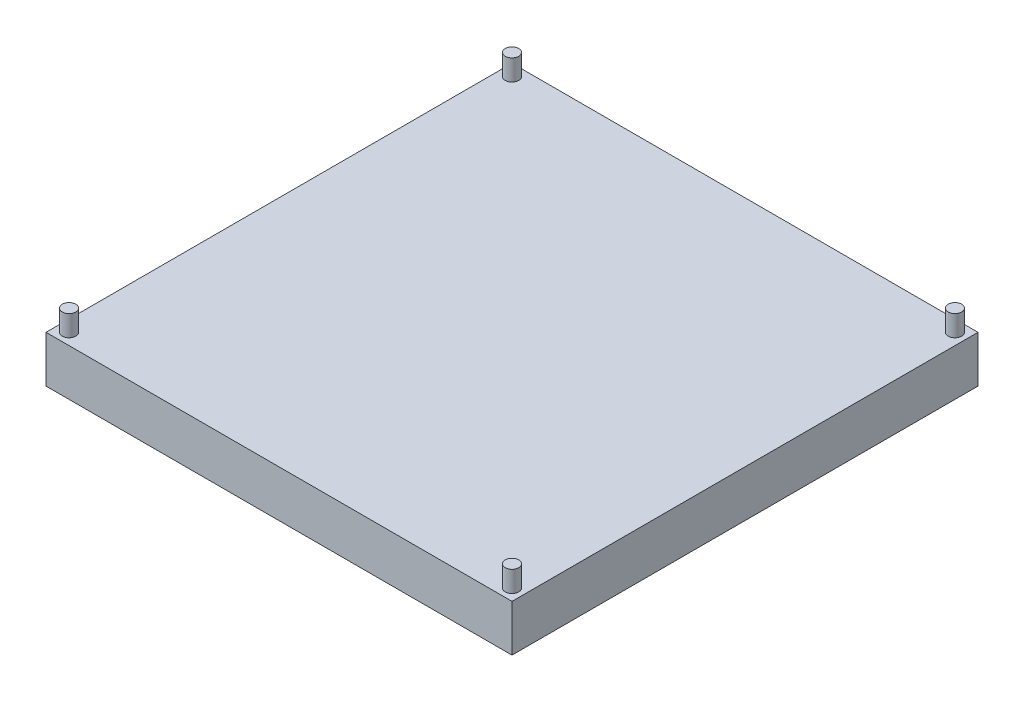
SolidWorks part; units mm, degrees
ref_plane "Front Plane" through (0, 0, 0) normal (0, 0, 1) x (1, 0, 0)
ref_plane "Top Plane" through (0, 0, 0) normal (0, 1, 0) x (1, 0, 0)
ref_plane "Right Plane" through (0, 0, 0) normal (1, 0, 0) x (0, 0, -1)
sketch "Sketch1" plane through (0, 0, 0) normal (0, 1, 0) x (1, 0, 0)
  line L1 (-25.4, -25.4) -> (25.4, -25.4)
  line L2 (-25.4, -25.4) -> (-25.4, 25.4)
  line L3 (-25.4, 25.4) -> (25.4, 25.4)
  line L4 (25.4, -25.4) -> (25.4, 25.4)
  line L5 (-25.4, -25.4) -> (25.4, 25.4) construction
  line L6 (-25.4, 25.4) -> (25.4, -25.4) construction
  point P0 (0, 0)
  dimension "D1" = 50.8
  dimension "D2" = 50.8
extrude "Boss-Extrude1" add sketch "Sketch1" along normal blind 5.08
sketch "Sketch11" plane through (0, 5.08, 0) normal (0, 1, 0) x (1, 0, 0)
  line L5 (-22.86, -22.86) -> (22.86, 22.86) construction
  line L6 (-22.86, 22.86) -> (22.86, -22.86) construction
  line L8 (-25.4, 25.4) -> (-22.86, 22.86) construction
  line L9 (0, -2.794) -> (0, 2.794) construction
  line L10 (-2.794, 0) -> (2.794, 0) construction
  circle A0 centre (-24.1428, 24.1428) radius 0.7366
  circle A1 centre (24.1428, 24.1428) radius 0.7366
  circle A2 centre (24.1428, -24.1428) radius 0.7366
  circle A3 centre (-24.1428, -24.1428) radius 0.7366
  point P0 (0, 0)
  dimension "D1" = 1.4732
  dimension "D3" = 1.778
extrude "Boss-Extrude2" add sketch "Sketch11" along normal blind 2.286
sketch "Sketch12" plane through (0, 0, 0) normal (0, -1, 0) x (1, 0, 0)
  line L0 (-25.4, 25.4) -> (25.4, 25.4) construction
  line L1 (-22.86, -22.86) -> (22.86, -22.86)
  line L2 (-22.86, -22.86) -> (-22.86, 22.86)
  line L3 (-22.86, 22.86) -> (22.86, 22.86)
  line L4 (22.86, -22.86) -> (22.86, 22.86)
  line L5 (-22.86, -22.86) -> (22.86, 22.86) construction
  line L6 (-22.86, 22.86) -> (22.86, -22.86) construction
  line L7 (-25.4, -25.4) -> (-25.4, 25.4) construction
  point P0 (0, 0)
  dimension "D1" = 2.54
  dimension "D2" = 2.54
extrude "Cut-Extrude1" cut sketch "Sketch12" against normal blind 1.27
